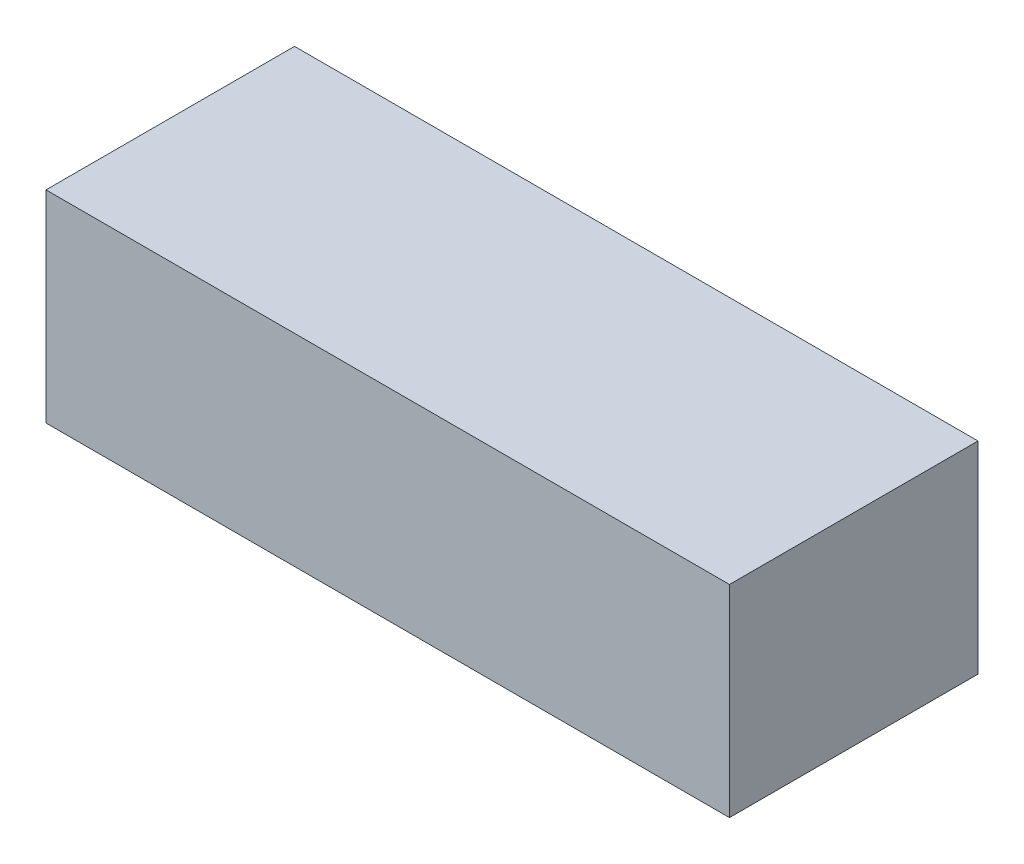
SolidWorks part; units mm, degrees
ref_plane "前视基准面" through (0, 0, 0) normal (0, 0, 1) x (1, 0, 0)
ref_plane "上视基准面" through (0, 0, 0) normal (0, 1, 0) x (1, 0, 0)
ref_plane "右视基准面" through (0, 0, 0) normal (1, 0, 0) x (0, 0, -1)
sketch "草图1" plane through (0, 0, 0) normal (0, 1, 0) x (1, 0, 0)
  line L1 (-22, 8) -> (22, 8)
  line L2 (-22, 8) -> (-22, -8)
  line L3 (-22, -8) -> (22, -8)
  line L4 (22, 8) -> (22, -8)
  line L5 (-22, 8) -> (22, -8) construction
  line L6 (-22, -8) -> (22, 8) construction
  point P0 (0, 0)
extrude "凸台-拉伸1" add sketch "草图1" against normal blind 2 contours L2 L1 L4 L3
sketch "草图2" plane through (0, -2, 0) normal (0, -1, 0) x (1, 0, 0)
  line L0 (-22, -8) -> (-22, 8) construction
  line L1 (-20, 6) -> (20, 6)
  line L2 (-20, 6) -> (-20, -6)
  line L3 (-20, -6) -> (20, -6)
  line L4 (20, 6) -> (20, -6)
  line L5 (-22, 8) -> (22, 8) construction
  line L6 (-22, -8) -> (22, -8) construction
  line L7 (22, -8) -> (22, 8) construction
  line L8 (-22, -8) -> (-22, 8)
  line L9 (-22, 8) -> (22, 8)
  line L10 (-22, -8) -> (22, -8)
  line L11 (22, -8) -> (22, 8)
  dimension "D1" = 12
  dimension "D2" = 40
  dimension "D3" = 2
  dimension "D4" = 2
extrude "凸台-拉伸2" add sketch "草图2" along normal blind 10
sketch "草图3" plane through (-22, 0, 0) normal (-1, 0, 0) x (0, 0, 1)
  line L0 (0, 0) -> (0, -12)
  line L1 (-5.5, -7) -> (5.5, -7)
  line L2 (-5.5, -7) -> (-5.5, -11)
  line L3 (-5.5, -11) -> (5.5, -11)
  line L4 (5.5, -7) -> (5.5, -11)
  line L5 (-5.5, -7) -> (5.5, -11) construction
  line L6 (-5.5, -11) -> (5.5, -7) construction
  line L7 (8, -12) -> (-8, -12) construction
  line L8 (-8, 0) -> (8, 0) construction
  point P0 (0, -9)
  dimension "D1" = 4
  dimension "D2" = 11
  dimension "D3" = 7
extrude "切除-拉伸1" cut sketch "草图3" against normal blind 2 contours L4 L1 L0 L3 | L2 L3 L0 L1
sketch "草图4" plane through (0, -2, 0) normal (0, -1, 0) x (1, 0, 0)
  line L0 (-20, -6) -> (20, -6) construction
  line L1 (-20, 6) -> (8, 6)
  line L2 (-20, 6) -> (-20, -6)
  line L3 (-20, -6) -> (8, -6)
  line L4 (8, 6) -> (8, -6)
  line L5 (20, -6) -> (20, 6) construction
  line L6 (-5.15, 6) -> (-6.85, 6)
  line L7 (-20, 6) -> (-18.3, 6)
  line L8 (-20, 6) -> (-20, -6)
  line L9 (-20, -6) -> (-18.3, -6)
  line L10 (-18.3, 6) -> (-18.3, -6)
  line L11 (8, 6) -> (6.3, 6)
  line L12 (8, 6) -> (8, -6)
  line L13 (8, -6) -> (6.3, -6)
  line L14 (6.3, 6) -> (6.3, -6)
  line L15 (-5.15, 6) -> (-5.15, -6)
  line L16 (-5.15, -6) -> (-6.85, -6)
  line L17 (-6.85, 6) -> (-6.85, -6)
  line M6 (-20, -6) -> (20, -6)
  line M8 (20, 6) -> (-20, 6)
  dimension "D1" = 12
  dimension "D2" = 1.7
  dimension "D3" = 1.7
  dimension "D4" = 0
  dimension "D5" = 24.6
  dimension "D6" = 11.45
  dimension "D7" = 11.45
extrude "凸台-拉伸4" add sketch "草图4" along normal blind 4.6 contours L14 L4 M8 M6 | L8 L7 L10 L9 | L6 L17 L16 L15
sketch "草图9" plane through (0, -12, 0) normal (0, -1, 0) x (1, 0, 0)
  line L0 (-22, 8) -> (-22, -8) construction
  line L1 (21, -7) -> (-21, -7)
  line L2 (21, -7) -> (21, 7)
  line L3 (21, 7) -> (-21, 7)
  line L4 (-21, -7) -> (-21, 7)
  line L5 (21, -7) -> (-21, 7) construction
  line L6 (21, 7) -> (-21, -7) construction
  line L7 (22, 8) -> (-22, 8) construction
  line L8 (22, -8) -> (22, 8) construction
  line L9 (-22, -8) -> (22, -8) construction
  line L10 (22, -8) -> (22, 8)
  line L11 (-22, -8) -> (22, -8)
  line L12 (-22, 8) -> (-22, -8)
  line L13 (22, 8) -> (-22, 8)
  point P0 (0, 0)
  dimension "D1" = 1
  dimension "D2" = 1
extrude "凸台-拉伸5" add sketch "草图9" along normal blind 1
sketch "草图11" plane through (0, -12, 0) normal (0, -1, 0) x (1, 0, 0)
  line L7 (-20, -6) -> (20, -6) construction
  line L8 (-20, -6) -> (21, -6)
  line L9 (21, -7) -> (21, 7) construction
sketch "草图12" plane through (0, -12, 0) normal (0, -1, 0) x (1, 0, 0)
  line L1 (20, 6) -> (21, 6)
  line L2 (20, 6) -> (20, -6)
  line L3 (20, -6) -> (21, -6)
  line L4 (21, 6) -> (21, -6)
extrude "切除-拉伸3" cut sketch "草图12" against normal blind 5
sketch "草图13" plane through (0, -13, 0) normal (0, -1, 0) x (1, 0, 0)
  line L1 (-20.6, -6.6) -> (20.6, -6.6)
  line L2 (-20.6, -6.6) -> (-20.6, 6.6)
  line L3 (-20.6, 6.6) -> (20.6, 6.6)
  line L4 (20.6, -6.6) -> (20.6, 6.6)
  line L5 (-20, -6) -> (20, -6)
  line L6 (-20, -6) -> (-20, 6)
  line L7 (-20, 6) -> (20, 6)
  line L8 (20, -6) -> (20, 6)
extrude "RevB_AssemblyClearance_41p2x13p2" cut sketch "草图13" against normal blind 11
sketch "草图14" plane through (-22, 0, 0) normal (-1, 0, 0) x (0, 0, 1)
  line L1 (-5.5, -14) -> (5.5, -14)
  line L2 (-5.5, -14) -> (-5.5, -7)
  line L3 (-5.5, -7) -> (5.5, -7)
  line L4 (5.5, -14) -> (5.5, -7)
extrude "RevB_USB_TopLoading_Uslot" cut sketch "草图14" against normal blind 2.1
sketch "草图17" plane through (8, 0, 0) normal (1, 0, 0) x (0, 0, -1)
  line L1 (-5.3, -6.61) -> (5.3, -6.61)
  line L2 (-5.3, -6.61) -> (-5.3, -5.6)
  line L3 (-5.3, -5.6) -> (5.3, -5.6)
  line L4 (5.3, -6.61) -> (5.3, -5.6)
extrude "RevB_UndersideSolderRelief_1mm" cut sketch "草图17" against normal blind 28
